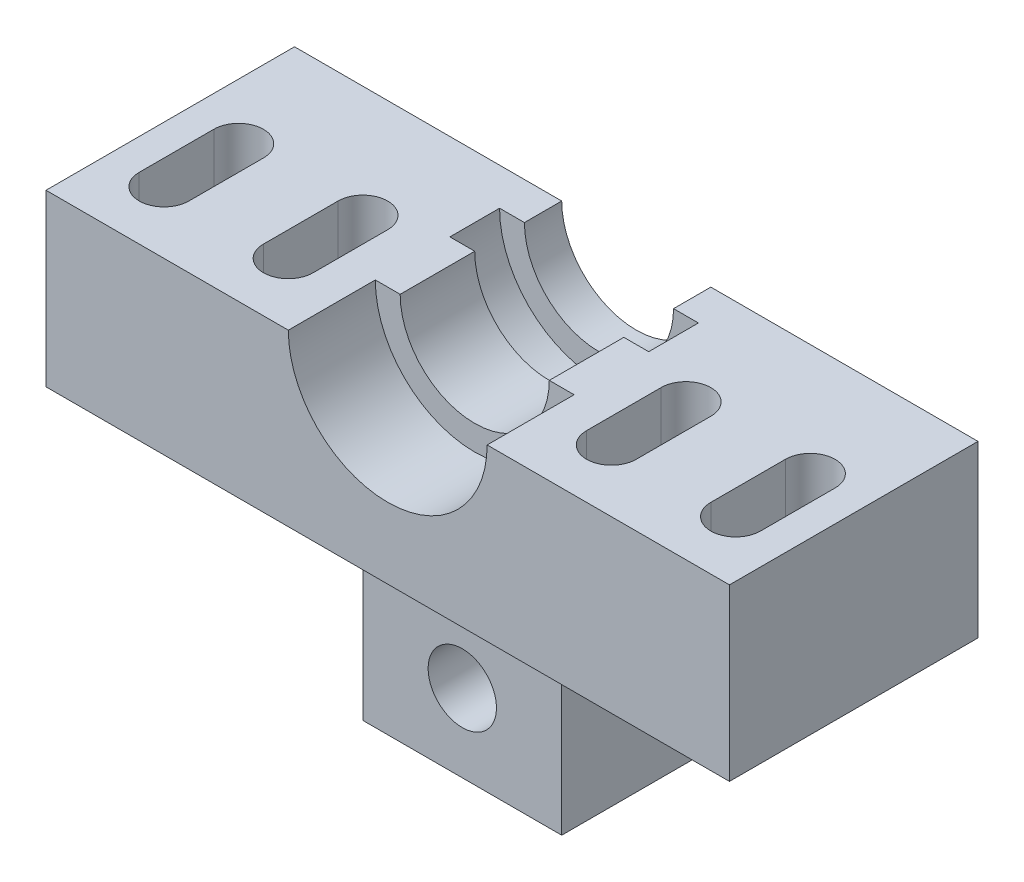
SolidWorks part; units mm, degrees
ref_plane "Front Plane" through (0, 0, 0) normal (0, 0, 1) x (1, 0, 0)
ref_plane "Top Plane" through (0, 0, 0) normal (0, 1, 0) x (1, 0, 0)
ref_plane "Right Plane" through (0, 0, 0) normal (1, 0, 0) x (0, 0, -1)
sketch "Sketch1" plane through (0, 0, 0) normal (0, 1, 0) x (1, 0, 0)
  line L0 (0, 0) -> (0, 7)
  line L1 (0, 7) -> (-2, 7)
  line L2 (-2, 7) -> (-2, 13)
  line L3 (-2, 13) -> (0, 13)
  line L4 (0, 13) -> (0, 17)
  line L5 (0, 17) -> (-2, 17)
  line L6 (4, 17) -> (4, 0)
  line L7 (4, 0) -> (0, 0)
  line L8 (-2, 17) -> (-2, 20)
  line L9 (-8, 0) -> (-8, 14.5552) construction
  line L10 (-2, 20) -> (4, 20)
  line L11 (4, 20) -> (4, 17)
  dimension "D1" = 7
  dimension "D2" = 6
  dimension "D3" = 8
  dimension "D4" = 4
  dimension "D5" = 12
  dimension "D6" = 6
  dimension "D7" = 3
revolve "Revolve1" add sketch "Sketch1" angle 180 about L9
sketch "Sketch8" plane through (0, 0, -20) normal (0, 0, -1) x (-1, 0, 0)
  line L0 (20, 0) -> (35.5, 0)
  line L1 (35.5, 0) -> (35.5, -13.7)
  line L2 (35.5, -13.7) -> (-19.5, -13.7)
  line L3 (-19.5, -13.7) -> (-19.5, 0)
  line L4 (-19.5, 0) -> (-4, 0)
  arc A0 (-4, 0) -> (20, 0) centre (8, 0) ccw
  dimension "D1" = 27.5
  dimension "D2" = 13.7
extrude "Boss-Extrude4" add sketch "Sketch8" against normal up to surface (20 mm away) up to face at (-8, -5, 0)
sketch "Sketch9" plane through (0, 0, 0) normal (0, 1, 0) x (1, 0, 0)
  line L0 (15, 8) -> (5, 8) construction
  line L2 (-35.5, 0) -> (-35.5, 20) construction
  line L3 (-31, 5) -> (-31, 11) construction
  line L4 (-33, 5) -> (-33, 11)
  line L5 (-29, 5) -> (-29, 11)
  line L6 (-26, 8) -> (-26, 12.6008) construction
  line L7 (-21, 5) -> (-21, 11) construction
  line L8 (-19, 5) -> (-19, 11)
  line L9 (-23, 5) -> (-23, 11)
  line L10 (-21, 8) -> (-31, 8) construction
  line L12 (-8, 10) -> (-8, 14.4685) construction
  line L13 (5, 5) -> (5, 11) construction
  line L14 (3, 5) -> (3, 11)
  line L15 (7, 5) -> (7, 11)
  line L16 (15, 5) -> (15, 11) construction
  line L17 (17, 5) -> (17, 11)
  line L18 (13, 5) -> (13, 11)
  line L20 (19.5, 0) -> (19.5, 20) construction
  arc A0 (-33, 5) -> (-29, 5) centre (-31, 5) ccw
  arc A1 (-29, 11) -> (-33, 11) centre (-31, 11) ccw
  arc A2 (-19, 5) -> (-23, 5) centre (-21, 5) cw
  arc A3 (-23, 11) -> (-19, 11) centre (-21, 11) cw
  arc A4 (3, 5) -> (7, 5) centre (5, 5) ccw
  arc A5 (7, 11) -> (3, 11) centre (5, 11) ccw
  arc A6 (17, 5) -> (13, 5) centre (15, 5) cw
  arc A7 (13, 11) -> (17, 11) centre (15, 11) cw
  point P8 (-31, 8)
  point P17 (-21, 8)
  point P25 (19.5, 10)
  point P29 (5, 8)
  point P36 (15, 8)
  dimension "D2" = 2
  dimension "D1" = 3
  dimension "D3" = 4.5
  dimension "D4" = 5
  dimension "D5" = 2
extrude "Cut-Extrude4" cut sketch "Sketch9" against normal blind 20
sketch "Sketch12" plane through (0, -13.7, 0) normal (0, -1, 0) x (-1, 0, 0)
  line L0 (-19.5, 20) -> (35.5, 20) construction
  line L2 (0, 18) -> (16, 18)
  line L3 (0, 18) -> (0, 6)
  line L4 (0, 6) -> (16, 6)
  line L5 (16, 18) -> (16, 6)
  line L6 (0, 18) -> (16, 6) construction
  line L7 (0, 6) -> (16, 18) construction
  point P4 (8, 12)
  dimension "D1" = 16
  dimension "D2" = 12
  dimension "D3" = 8
extrude "Boss-Extrude6" add sketch "Sketch12" along normal blind 16.5
sketch "Sketch13" plane through (0, -30.2, 0) normal (0, -1, 0) x (-1, 0, 0)
  line L0 (0, 18) -> (16, 6) construction
  line L2 (4, 14) -> (12, 14)
  line L3 (4, 14) -> (4, 10)
  line L4 (4, 10) -> (12, 10)
  line L5 (12, 14) -> (12, 10)
  line L6 (4, 14) -> (12, 10) construction
  line L7 (4, 10) -> (12, 14) construction
  point P4 (8, 12)
  dimension "D1" = 8
  dimension "D2" = 4
extrude "Cut-Extrude6" cut sketch "Sketch13" against normal blind 15
sketch "Sketch14" plane through (0, 0, -18) normal (0, 0, -1) x (-1, 0, 0)
  line L0 (8, -13.7) -> (8, -17.7) construction
  line L3 (0, -13.7) -> (16, -13.7) construction
  line L4 (8, -17.7) -> (8, -30.2) construction
  line L5 (0, -30.2) -> (16, -30.2) construction
  circle A0 centre (8, -23.95) radius 2.75
  point P4 (0, 0)
  point P10 (8, -23.95)
  dimension "D2" = 5.5
  dimension "D1" = 4
extrude "Cut-Extrude7" cut sketch "Sketch14" against normal blind 15
